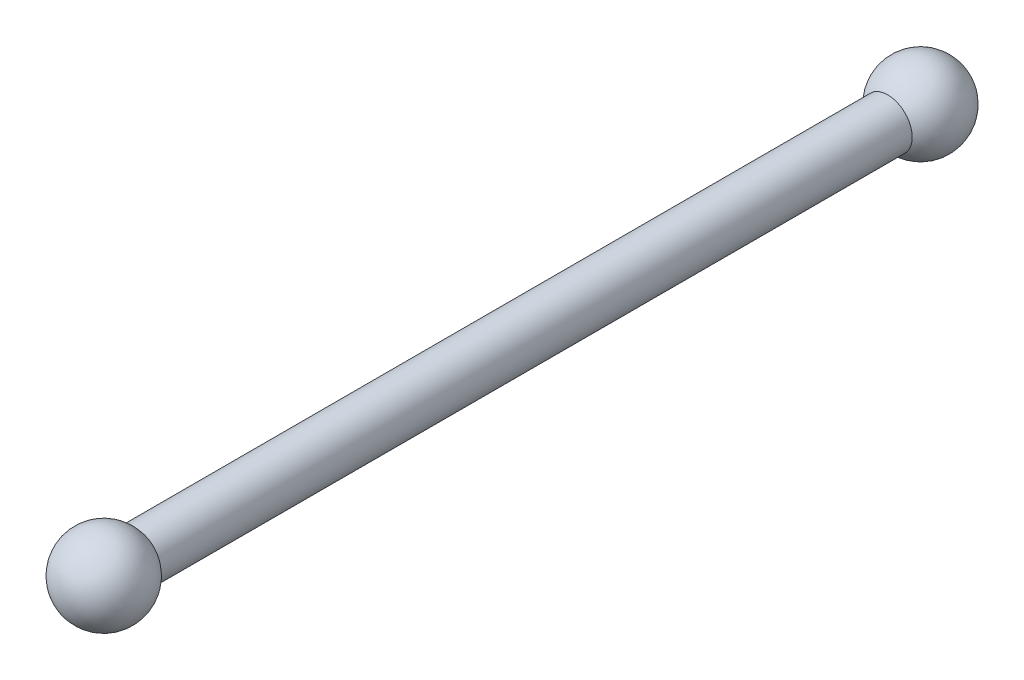
SolidWorks part; units mm, degrees
ref_plane "Płaszczyzna przednia" through (0, 0, 0) normal (0, 0, 1) x (1, 0, 0)
ref_plane "Płaszczyzna górna" through (0, 0, 0) normal (0, 1, 0) x (1, 0, 0)
ref_plane "Płaszczyzna prawa" through (0, 0, 0) normal (1, 0, 0) x (0, 0, -1)
sketch "Szkic1" plane through (0, 0, 0) normal (0, 0, 1) x (1, 0, 0)
  circle A0 centre (0, 0) radius 1.5
  dimension "D1" = 3
extrude "Dodanie-wyciągnięcie1" add sketch "Szkic1" along normal mid plane 50
sketch "Szkic2" plane through (0, 0, 0) normal (0, 1, 0) x (1, 0, 0)
  line L0 (0, 0) -> (0, 25)
  line L1 (0, 0) -> (0, -25)
  line L2 (0, -25) -> (0, -27.5)
  line L3 (0, 25) -> (0, 27.5)
  arc A0 (0, 22.5) -> (0, 27.5) centre (0, 25) ccw
  arc A1 (0, -27.5) -> (0, -22.5) centre (0, -25) ccw
  dimension "D3" = 5
  dimension "D4" = 5
  dimension "D1" = 25
  dimension "D2" = 25
revolve "Obrót1" add sketch "Szkic2" angle 360 about L0
